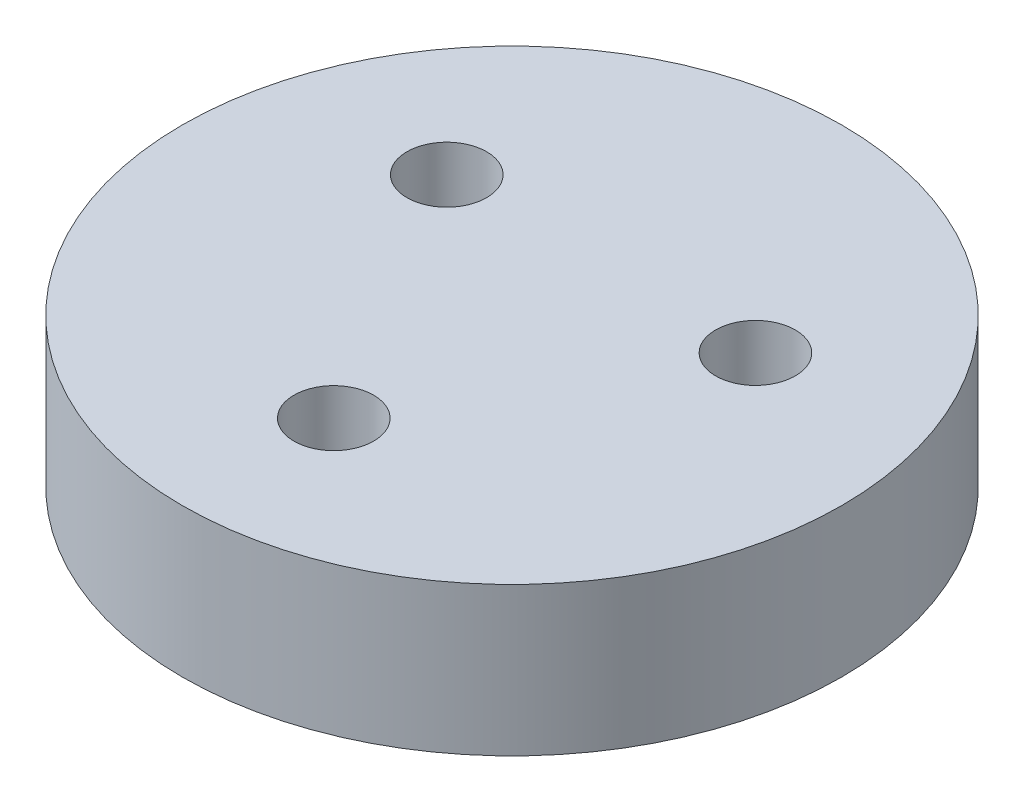
SolidWorks part; units mm, degrees
ref_plane "Front Plane" through (0, 0, 0) normal (0, 0, 1) x (1, 0, 0)
ref_plane "Top Plane" through (0, 0, 0) normal (0, 1, 0) x (1, 0, 0)
ref_plane "Right Plane" through (0, 0, 0) normal (1, 0, 0) x (0, 0, -1)
sketch "Sketch4" plane through (0, 0, 0) normal (0, 1, 0) x (1, 0, 0)
  circle A0 centre (0, 0) radius 33.3
  dimension "D1" = 66.6
extrude "Boss-Extrude2" add sketch "Sketch4" along normal blind 15
sketch "Sketch5" plane through (0, 0, 0) normal (0, -1, 0) x (1, 0, 0)
  circle A0 centre (0, 18) radius 4.025
  circle A1 centre (15.5885, -9) radius 4.025
  circle A2 centre (-15.5885, -9) radius 4.025
  point P10 (0, 0)
  dimension "D1" = 8.05
  dimension "D2" = 18
extrude "Cut-Extrude1" cut sketch "Sketch5" against normal through all
sketch "Sketch6" plane through (0, 0, 0) normal (0, -1, 0) x (1, 0, 0)
  circle A0 centre (0, 0) radius 7.5
  dimension "D1" = 15
extrude "Boss-Extrude3" add sketch "Sketch6" along normal blind 10
fillet "Fillet1" radius 2.5 1 edges at (0, 0, 7.5)
